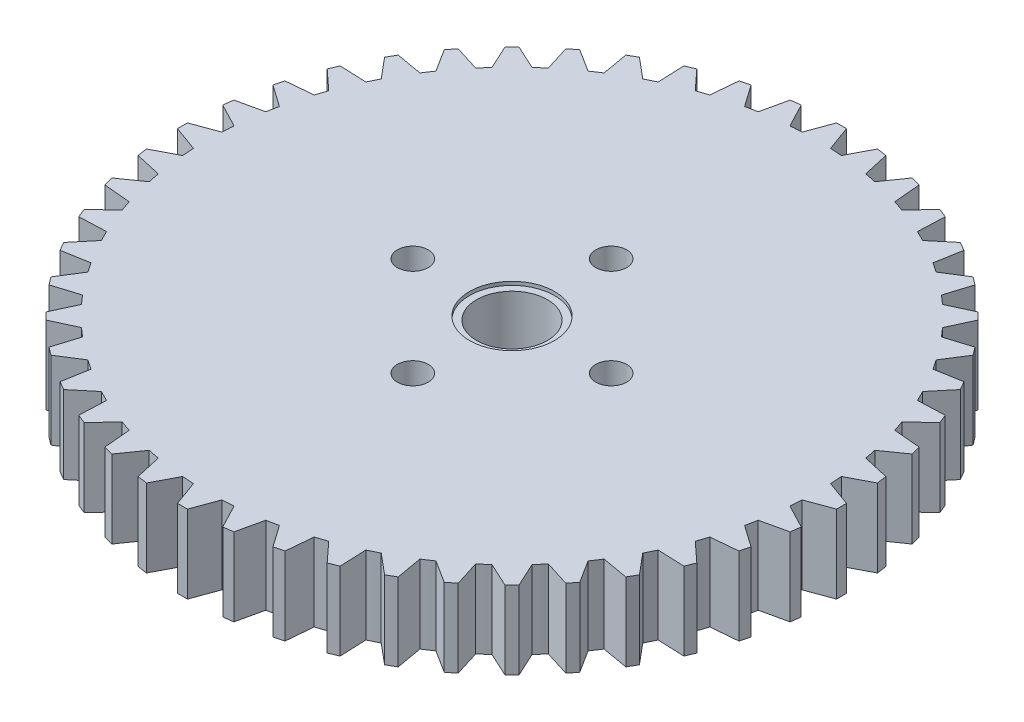
SolidWorks part; units mm, degrees
material "ABS"
ref_plane "Front" through (0, 0, 0) normal (0, 0, 1) x (1, 0, 0)
ref_plane "Top" through (0, 0, 0) normal (0, 1, 0) x (1, 0, 0)
ref_plane "Right" through (0, 0, 0) normal (1, 0, 0) x (0, 0, -1)
sketch "Sketch2" plane through (0, 0, 0) normal (0, 1, 0) x (1, 0, 0)
  circle A0 centre (0, 0) radius 21.5
  circle A1 centre (0, 0) radius 2.5
  dimension "D1" = 43
  dimension "D2" = 5
extrude "Boss-Extrude1" add sketch "Sketch2" along normal blind 5.5
ref_plane "Plane1" through (0, 3, 0) normal (0, 1, 0) x (1, 0, 0)
sketch "Sketch3" plane through (0, 3, 0) normal (0, 1, 0) x (1, 0, 0)
  line L0 (0, 21.5) -> (0, -21.5) construction
  line L1 (-21.5, 0) -> (21.5, 0) construction
  line L3 (0, 21.5) -> (0, 23.25) construction
  line L4 (-1, 21.4767) -> (-0.35, 23.25)
  line L5 (-0.35, 23.25) -> (0.35, 23.25)
  line L6 (1, 21.4767) -> (0.35, 23.25)
  circle A0 centre (0, 0) radius 21.5 construction
  arc A1 (-21.5, 0) -> (21.5, 0) centre (0, 0) ccw
  arc A2 (1, 21.4767) -> (-1, 21.4767) centre (0, 0) ccw
  dimension "D1" = 2
  dimension "D2" = 0.35
  dimension "D3" = 23.25
extrude "Boss-Extrude2" add sketch "Sketch3" along normal blind 2.5 and the other way blind 3 contours L6 L5 L4 A2
pattern_circular "CirPattern1" count 48 over 360 about axis through (0, 0, 0) along (0, 1, 0) of "Boss-Extrude2"
sketch "Sketch4" plane through (0, 5.5, 0) normal (0, 1, 0) x (1, 0, 0)
  circle A0 centre (0, 0) radius 3
  circle A1 centre (0, 0) radius 2.5
  circle A2 centre (0, 0) radius 2.5 construction
  dimension "D1" = 0.5
extrude "Cut-Extrude1" cut sketch "Sketch4" against normal blind 0.25
ref_plane "Plane2" through (0, 5.5, 0) normal (0, 1, 0) x (1, 0, 0)
sketch "Sketch5" plane through (0, 5.5, 0) normal (0, 1, 0) x (1, 0, 0)
  line L0 (-34.259, 0) -> (34.259, 0) construction
  line L1 (0, -34.259) -> (0, 34.259) construction
  circle A0 centre (0, 7) radius 1.09
  point P6 (0, 0)
  dimension "D1" = 7
  dimension "D2" = 2.18
extrude "Cut-Extrude2" cut sketch "Sketch5" against normal up to surface (5.5 mm away) up to face at (0, 0, 0)
pattern_circular "CirPattern2" count 4 over 360 about axis through (0, 0, 0) along (0, 1, 0) of "Cut-Extrude2"
